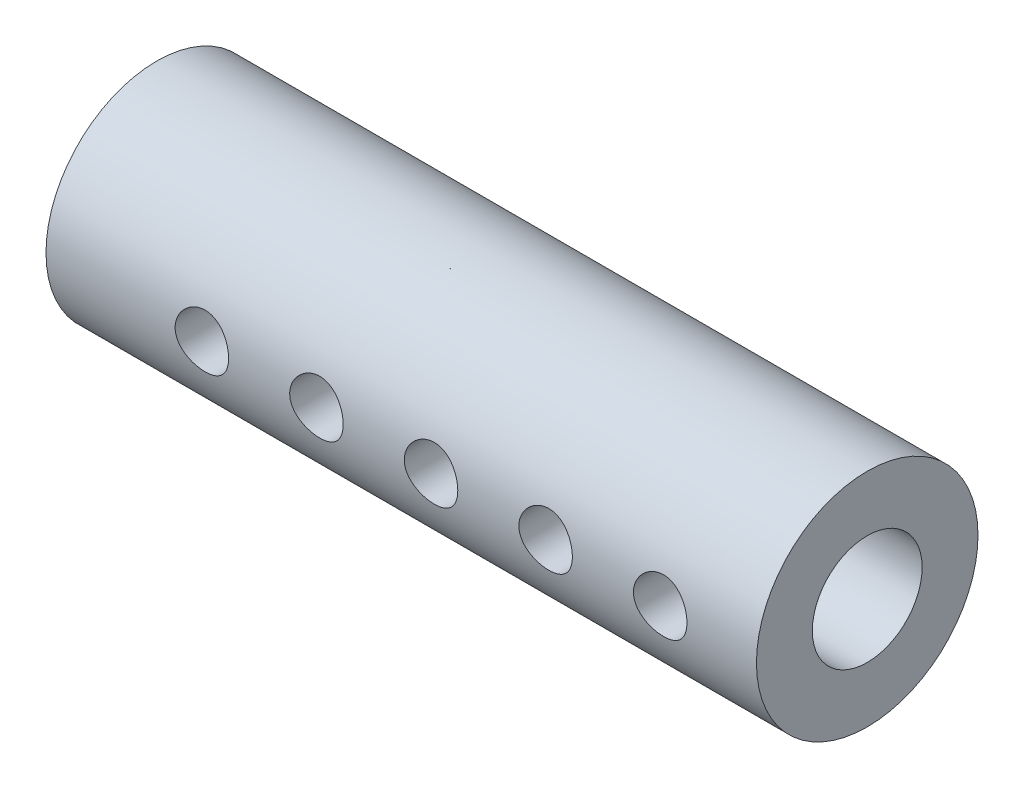
SolidWorks part; units mm, degrees
ref_plane "Front Plane" through (0, 0, 0) normal (0, 0, 1) x (1, 0, 0)
ref_plane "Top Plane" through (0, 0, 0) normal (0, 1, 0) x (1, 0, 0)
ref_plane "Right Plane" through (0, 0, 0) normal (1, 0, 0) x (0, 0, -1)
sketch "Sketch1" plane through (0, 0, 0) normal (1, 0, 0) x (0, 0, -1)
  circle A0 centre (0, 0) radius 18.415
  dimension "D1" = 36.83
extrude "Boss-Extrude1" add sketch "Sketch1" along normal blind 118.11
sketch "Sketch2" plane through (0, 0, 0) normal (-1, 0, 0) x (0, 0, 1)
  circle A0 centre (0, 0) radius 9.1281
  point P2 (0, 0)
  point P4 (1.6655, 0.4763)
  dimension "D1" = 18.2562
extrude "Cut-Extrude1" cut sketch "Sketch2" against normal up to surface (118.11 mm away) up to face at (118.11, 0, -18.415)
ref_plane "Plane1" through (14.478, 0, 0) normal (-1, 0, 0) x (0, 0, 1)
sketch "Sketch3" plane through (0, 0, 0) normal (-1, 0, 0) x (0, 0, 1)
  line L0 (0, 0) -> (14.1067, -11.8369)
  line L1 (0, 0) -> (18.415, 0)
  circle A0 centre (0, 0) radius 18.415 construction
  dimension "D1" = 40
ref_plane "Plane2" through (0, 0, 18.415) normal (0, 0, 1) x (1, 0, 0)
sketch "Sketch4" plane through (0, 0, 18.415) normal (0, 0, 1) x (1, 0, 0)
  line L0 (14.478, 0) -> (118.11, 0) construction
  line L1 (14.478, 20.2565) -> (14.478, -20.2565) construction
  line L2 (118.11, -18.415) -> (118.11, 18.415) construction
  circle A0 centre (25.908, 0) radius 4.445
  dimension "D1" = 8.89
  dimension "D2" = 11.43
extrude "Cut-Extrude2" cut sketch "Sketch4" against normal up to surface (9.2869 mm away) contours A0 up to face at (0, 0, 9.1281)
pattern_linear "LPattern1" count 5 spacing 19.05 along (1, 0, 0) of "Cut-Extrude2"
